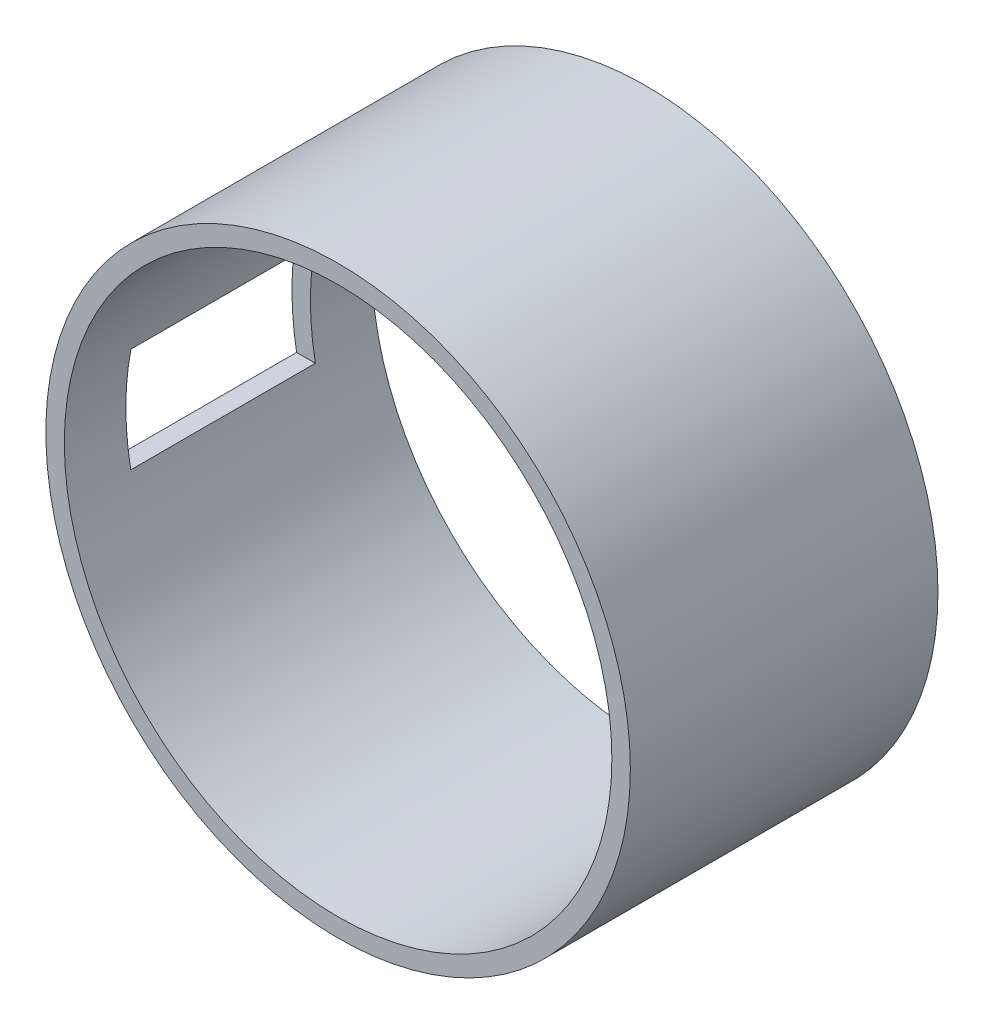
SolidWorks part; units mm, degrees
ref_plane "前视基准面" through (0, 0, 0) normal (0, 0, 1) x (1, 0, 0)
ref_plane "上视基准面" through (0, 0, 0) normal (0, 1, 0) x (1, 0, 0)
ref_plane "右视基准面" through (0, 0, 0) normal (1, 0, 0) x (0, 0, -1)
sketch "草图1" plane through (0, 0, 0) normal (0, 0, 1) x (1, 0, 0)
  circle A0 centre (0, 0) radius 8.9
  circle A1 centre (0, 0) radius 9.5
  dimension "D1" = 17.8
  dimension "D2" = 19
extrude "凸台-拉伸1" add sketch "草图1" along normal blind 10
sketch "草图2" plane through (0, 0, 10) normal (0, 0, 1) x (1, 0, 0)
  line L0 (-9.5, 0) -> (-8.9, 0) construction
  circle A0 centre (0, 0) radius 9.5 construction
  circle A1 centre (0, 0) radius 8.9 construction
ref_plane "基准面1" through (-9.5, 0, 0) normal (-1, 0, 0) x (0, 0, 1)
sketch "草图3" plane through (-9.5, 0, 0) normal (-1, 0, 0) x (0, 0, 1)
  line L0 (0, 0) -> (2, 0) construction
  line L1 (2, 0) -> (2, 1.7148) construction
  line L3 (2, 1.7148) -> (8, 1.7148)
  line L4 (2, 1.7148) -> (2, -1.6852)
  line L5 (2, -1.6852) -> (8, -1.6852)
  line L6 (8, 1.7148) -> (8, -1.6852)
  dimension "D1" = 6
  dimension "D2" = 3.4
extrude "切除-拉伸1" cut sketch "草图3" against normal blind 1.5
